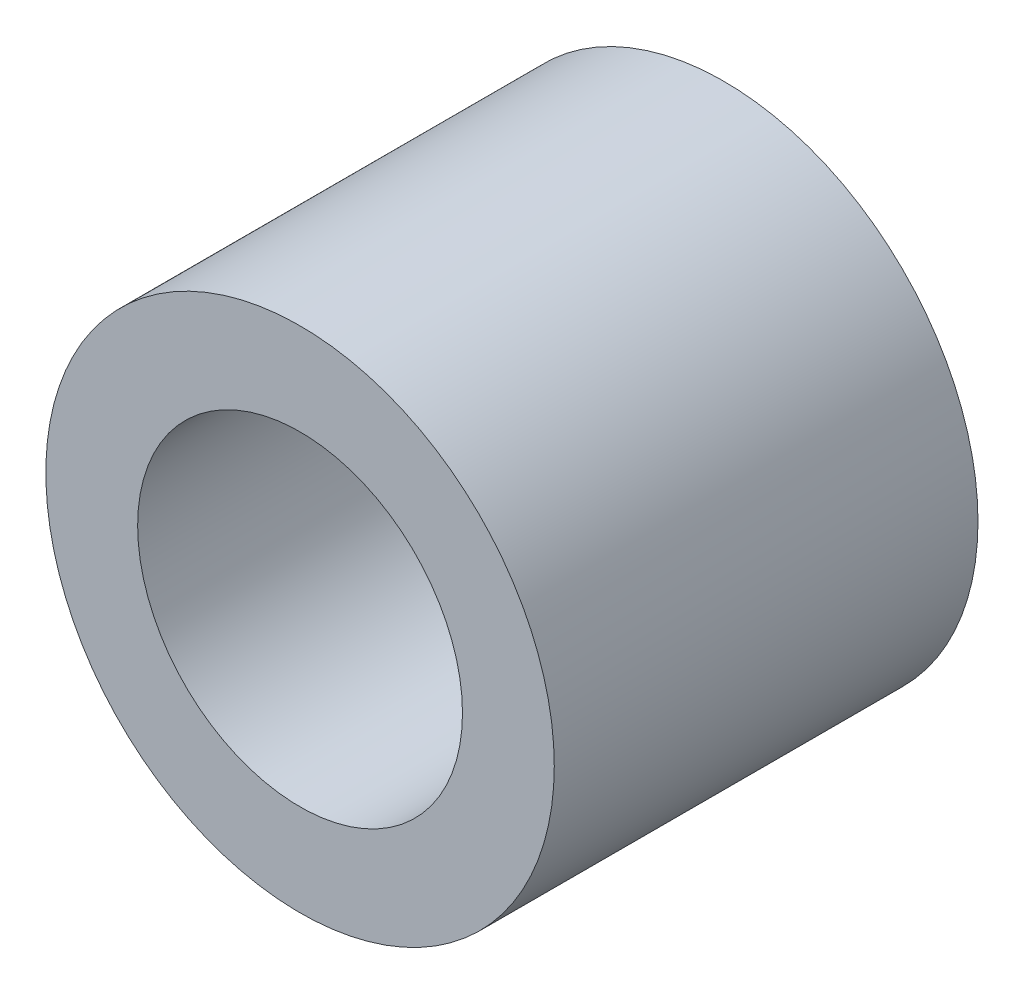
SolidWorks part; units mm, degrees
ref_plane "Front" through (0, 0, 0) normal (0, 0, 1) x (1, 0, 0)
ref_plane "Top" through (0, 0, 0) normal (0, 1, 0) x (1, 0, 0)
ref_plane "Right" through (0, 0, 0) normal (1, 0, 0) x (0, 0, -1)
sketch "Skizze1" plane through (0, 0, 0) normal (0, 0, 1) x (1, 0, 0)
  circle A0 centre (0, 0) radius 2.3
  circle A1 centre (0, 0) radius 3.6
  dimension "D1" = 7.2
  dimension "D2" = 4.6
extrude "Aufsatz-Linear austragen1" add sketch "Skizze1" along normal blind 6
